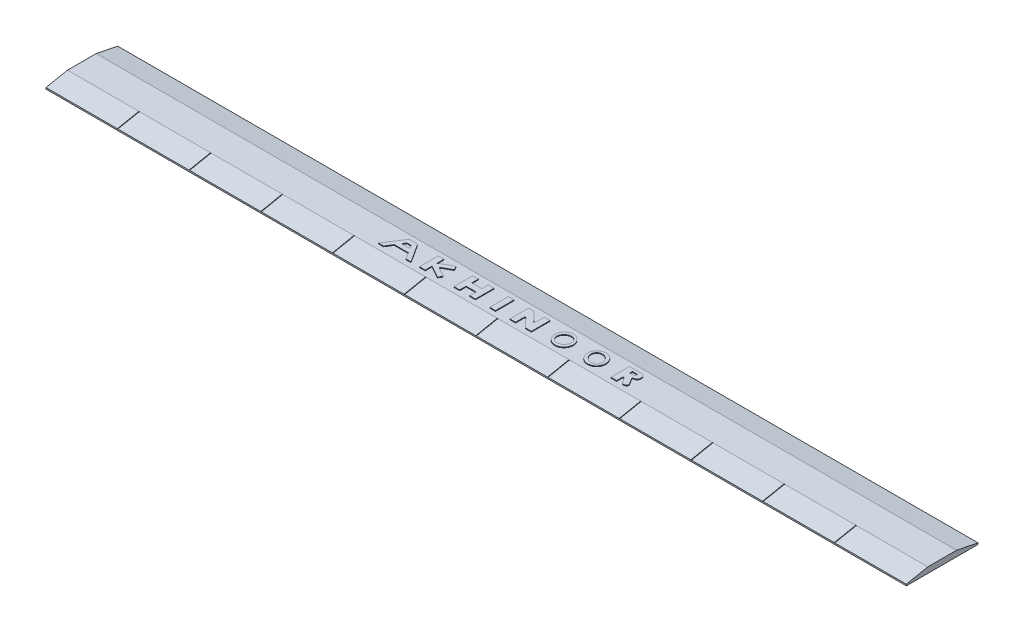
SolidWorks part; units mm, degrees
ref_plane "Front Plane" through (0, 0, 0) normal (0, 0, 1) x (1, 0, 0)
ref_plane "Top Plane" through (0, 0, 0) normal (0, 1, 0) x (1, 0, 0)
ref_plane "Right Plane" through (0, 0, 0) normal (1, 0, 0) x (0, 0, -1)
sketch "Sketch1" plane through (0, 0, 0) normal (0, 1, 0) x (1, 0, 0)
  line L0 (0, 0) -> (-304.8, 0)
  line L1 (-304.8, 0) -> (-304.8, 25.4)
  line L2 (-304.8, 25.4) -> (0, 25.4)
  line L3 (0, 25.4) -> (0, 0)
  dimension "D1" = 304.8
  dimension "D2" = 25.4
extrude "Boss-Extrude1" add sketch "Sketch1" along normal blind 2.032
sketch "Sketch2" plane through (0, 0, 0) normal (1, 0, 0) x (0, 0, -1)
  line L0 (0, 0.508) -> (7.62, 2.032)
  line L1 (0, 2.032) -> (0, 0) construction
  line L3 (0, 2.032) -> (25.4, 2.032) construction
  line L4 (17.78, 2.032) -> (25.4, 0.508)
  line L5 (25.4, 2.032) -> (25.4, 0) construction
  line L6 (25.4, 0.508) -> (25.4, 0)
  line L7 (25.4, 0) -> (0, 0)
  line L8 (0, 0) -> (0, 0.508)
  line L10 (7.62, 2.032) -> (12.7, 2.032)
  line L11 (17.78, 2.032) -> (12.7, 2.032)
  dimension "D1" = 0.508
  dimension "D2" = 5.08
extrude "Cut-Extrude2" cut sketch "Sketch2" against normal through all flip side to cut
sketch "Sketch4" plane through (0, 2.032, 0) normal (0, 1, 0) x (1, 0, 0)
  line L0 (-152.4, 17.78) -> (-152.4, 7.62) construction
  line L1 (-304.8, 17.78) -> (0, 17.78) construction
  line L2 (-304.8, 7.62) -> (0, 7.62) construction
  line L3 (-304.8, 16.002) -> (-144.272, 16.002) construction
  line L4 (-304.8, 17.78) -> (-304.8, 7.62) construction
  line L5 (0, 7.62) -> (0, 17.78) construction
  line L6 (0, 16.002) -> (0, 9.398)
  line L7 (0, 9.398) -> (-304.8, 9.398) construction
  line L8 (-304.8, 9.398) -> (-304.8, 16.002) construction
  line L9 (-304.8, 12.7) -> (-194.2687, 12.7) construction
  line L11 (-156.972, 16.002) -> (-154.94, 16.002)
  line L12 (-156.972, 16.002) -> (-156.972, 9.398)
  line L13 (-156.972, 9.398) -> (-154.94, 9.398)
  line L14 (-154.94, 16.002) -> (-154.94, 9.398)
  line L15 (-156.972, 16.002) -> (-154.94, 9.398) construction
  line L16 (-156.972, 9.398) -> (-154.94, 16.002) construction
  line L17 (-164.084, 16.002) -> (-162.052, 16.002)
  line L18 (-164.084, 16.002) -> (-164.084, 9.398)
  line L19 (-164.084, 9.398) -> (-162.052, 9.398)
  line L20 (-162.052, 16.002) -> (-162.052, 9.398)
  line L21 (-164.084, 16.002) -> (-162.052, 9.398) construction
  line L22 (-164.084, 9.398) -> (-162.052, 16.002) construction
  line L23 (-167.64, 13.716) -> (-164.084, 13.716)
  line L24 (-167.64, 13.716) -> (-167.64, 11.684)
  line L25 (-167.64, 11.684) -> (-164.084, 11.684)
  line L26 (-164.084, 13.716) -> (-164.084, 11.684)
  line L27 (-167.64, 13.716) -> (-164.084, 11.684) construction
  line L28 (-167.64, 11.684) -> (-164.084, 13.716) construction
  line L29 (-169.672, 16.002) -> (-167.64, 16.002)
  line L30 (-169.672, 16.002) -> (-169.672, 9.398)
  line L31 (-169.672, 9.398) -> (-167.64, 9.398)
  line L32 (-167.64, 16.002) -> (-167.64, 9.398)
  line L33 (-169.672, 16.002) -> (-167.64, 9.398) construction
  line L34 (-169.672, 9.398) -> (-167.64, 16.002) construction
  line L35 (-179.832, 16.002) -> (-181.864, 16.002)
  line L36 (-179.832, 16.002) -> (-179.832, 9.398)
  line L37 (-179.832, 9.398) -> (-181.864, 9.398)
  line L38 (-181.864, 16.002) -> (-181.864, 9.398)
  line L39 (-179.832, 16.002) -> (-181.864, 9.398) construction
  line L40 (-179.832, 9.398) -> (-181.864, 16.002) construction
  line L46 (-189.1051, 16.002) -> (-190.6291, 16.002)
  line L47 (-149.86, 16.002) -> (-147.828, 16.002)
  line L48 (-149.86, 16.002) -> (-149.86, 9.398)
  line L49 (-149.86, 9.398) -> (-147.828, 9.398)
  line L50 (-147.828, 12.4056) -> (-147.828, 9.398)
  line L51 (-149.86, 16.002) -> (-147.828, 9.398) construction
  line L52 (-149.86, 9.398) -> (-147.828, 16.002) construction
  line L54 (-144.272, 16.002) -> (-144.272, 12.8787)
  line L55 (-144.272, 9.398) -> (-142.24, 9.398)
  line L56 (-142.24, 16.002) -> (-142.24, 9.398)
  line L57 (-108.5727, 10.4151) -> (-110.0035, 12.7339)
  line L58 (-142.24, 16.002) -> (0, 16.002) construction
  line L59 (-111.7665, 13.97) -> (-110.4965, 13.97)
  line L60 (-114.0525, 9.398) -> (-112.0205, 9.398)
  line L61 (-114.0525, 9.398) -> (-114.0525, 16.002)
  line L62 (-114.0525, 16.002) -> (-111.1357, 16.002)
  line L63 (-112.0205, 9.398) -> (-112.0205, 11.3557)
  line L64 (-109.7345, 16.002) -> (-111.1357, 16.002)
  line L74 (-111.7665, 14.986) -> (-110.4965, 14.986)
  line L75 (-110.2425, 14.224) -> (-110.2425, 14.732)
  line L76 (-112.0205, 14.732) -> (-112.0205, 14.224)
  line L77 (-108.4645, 14.732) -> (-108.4645, 14.3913)
  line L78 (-109.7345, 13.1213) -> (-109.7873, 13.1213)
  line L79 (-179.832, 12.7) -> (-179.832, 16.002) construction
  line L80 (-179.7014, 13.6616) -> (-175.4926, 16.002)
  line L81 (-175.4926, 16.002) -> (-174.8754, 14.8921)
  line L82 (-174.974, 14.5466) -> (-177.8956, 12.922)
  line L84 (-177.8956, 12.478) -> (-174.974, 10.8534)
  line L85 (-174.8754, 10.5079) -> (-175.4926, 9.398)
  line L86 (-175.4926, 9.398) -> (-179.7014, 11.7384)
  line L87 (-179.832, 11.9604) -> (-179.832, 12.7)
  line L88 (-179.832, 12.7) -> (-179.832, 13.4396)
  line L89 (-189.1051, 16.002) -> (-184.8739, 9.398)
  line L94 (-184.8739, 9.398) -> (-186.6519, 9.398)
  line L98 (-194.6064, 9.398) -> (-196.3844, 9.398)
  line L99 (-196.3844, 9.398) -> (-192.1531, 16.002)
  line L101 (-190.6291, 16.002) -> (-192.1531, 16.002)
  line L102 (-186.9895, 12.7) -> (0, 12.7) construction
  line L103 (-194.6064, 9.398) -> (-193.2078, 11.6077)
  line L105 (-190.007, 14.478) -> (-191.2513, 14.478)
  line L107 (-189.7923, 14.3598) -> (-189.3366, 13.6397)
  line L108 (-191.7071, 13.2499) -> (-189.5512, 13.2499)
  line L110 (-188.2651, 11.7259) -> (-192.9932, 11.7259)
  line L112 (-191.9217, 13.6397) -> (-191.4659, 14.3598)
  line L113 (-188.0505, 11.6077) -> (-186.6519, 9.398)
  line L114 (-147.3894, 12.5801) -> (-144.4566, 9.4775)
  line L115 (-144.7106, 12.7042) -> (-147.828, 16.002)
  line L116 (-144.272, 16.002) -> (-142.24, 16.002)
  line L118 (-111.561, 11.5049) -> (-110.1647, 9.5826)
  arc A0 (-109.7345, 13.1213) -> (-108.4645, 14.3913) centre (-109.7345, 14.3913) ccw
  arc A1 (-109.7345, 16.002) -> (-108.4645, 14.732) centre (-109.7345, 14.732) cw
  arc A3 (-192.9932, 11.7259) -> (-193.2078, 11.6077) centre (-192.9932, 11.4719) ccw
  arc A4 (-188.0505, 11.6077) -> (-188.2651, 11.7259) centre (-188.2651, 11.4719) ccw
  arc A5 (-191.7071, 13.2499) -> (-191.9217, 13.6397) centre (-191.7071, 13.5039) cw
  arc A6 (-191.2513, 14.478) -> (-191.4659, 14.3598) centre (-191.2513, 14.224) ccw
  arc A7 (-189.7923, 14.3598) -> (-190.007, 14.478) centre (-190.007, 14.224) ccw
  arc A8 (-189.5512, 13.2499) -> (-189.3366, 13.6397) centre (-189.5512, 13.5039) ccw
  arc A9 (-174.8754, 14.8921) -> (-174.974, 14.5466) centre (-175.0974, 14.7686) cw
  arc A10 (-174.974, 10.8534) -> (-174.8754, 10.5079) centre (-175.0974, 10.6314) cw
  arc A11 (-179.7014, 11.7384) -> (-179.832, 11.9604) centre (-179.578, 11.9604) cw
  arc A12 (-179.7014, 13.6616) -> (-179.832, 13.4396) centre (-179.578, 13.4396) ccw
  arc A13 (-177.8956, 12.478) -> (-177.8956, 12.922) centre (-177.7722, 12.7) cw
  arc A14 (-144.4566, 9.4775) -> (-144.272, 9.398) centre (-144.272, 9.652) ccw
  arc A15 (-147.3894, 12.5801) -> (-147.828, 12.4056) centre (-147.574, 12.4056) ccw
  arc A16 (-144.7106, 12.7042) -> (-144.272, 12.8787) centre (-144.526, 12.8787) ccw
  arc A17 (-112.0205, 14.224) -> (-111.7665, 13.97) centre (-111.7665, 14.224) ccw
  arc A18 (-112.0205, 14.732) -> (-111.7665, 14.986) centre (-111.7665, 14.732) cw
  arc A19 (-110.4965, 14.986) -> (-110.2425, 14.732) centre (-110.4965, 14.732) cw
  arc A20 (-110.2425, 14.224) -> (-110.4965, 13.97) centre (-110.4965, 14.224) cw
  arc A21 (-110.0035, 12.7339) -> (-109.7873, 13.1213) centre (-109.7873, 12.8673) cw
  arc A23 (-112.0205, 11.3557) -> (-111.561, 11.5049) centre (-111.7665, 11.3557) cw
  arc A25 (-110.1647, 9.5826) -> (-108.5727, 10.4151) centre (-109.6349, 10.5079) ccw
  ellipse E0 centre (-133.9231, 12.7) end of major axis (-133.9231, 9.398) minor radius 3.2369
  ellipse E1 centre (-133.9231, 12.7) end of major axis (-132.0191, 14.2717) minor radius 2.1571
  ellipse E2 centre (-122.3694, 12.7) end of major axis (-124.2733, 14.2717) minor radius 2.1571
  ellipse E3 centre (-122.3694, 12.7) end of major axis (-122.3694, 9.398) minor radius 3.2369
  point P16 (-155.956, 12.7)
  point P21 (-163.068, 12.7)
  point P26 (-165.862, 12.7)
  point P31 (-168.656, 12.7)
  point P36 (-180.848, 12.7)
  point P41 (-189.484, 12.7)
  point P46 (-148.844, 12.7)
  point P101 (-178.2948, 12.7)
  point P107 (-190.6291, 11.7259)
  point P113 (-190.6291, 13.2499)
  point P114 (-190.6291, 14.478)
  point P120 (-108.4645, 13.1213)
  point P123 (-108.4645, 16.002)
  point P131 (-192.1684, 13.2499)
  point P134 (-191.3911, 14.478)
  point P137 (-189.8671, 14.478)
  point P140 (-189.0898, 13.2499)
  point P143 (-174.752, 14.6701)
  point P146 (-174.752, 10.7299)
  point P149 (-179.832, 11.811)
  point P152 (-179.832, 13.589)
  point P155 (-178.2948, 12.7)
  point P164 (-112.0205, 13.97)
  point P171 (-110.2425, 13.97)
  point P174 (-110.2425, 13.1213)
  point P177 (-110.0306, 9.398)
  point P180 (-112.0205, 12.1376)
  dimension "D15" = 1.27
  dimension "D33" = 1.27
  dimension "D37" = 0.254
  dimension "D1" = 1.778
  dimension "D2" = 1.778
  dimension "D3" = 2.032
  dimension "D4" = 0
  dimension "D5" = 7.62
  dimension "D6" = 5.08
  dimension "D7" = 5.08
  dimension "D8" = 2.54
  dimension "D9" = 7.62
  dimension "D10" = 5.08
  dimension "D11" = 5.08
  dimension "D12" = 5.08
  dimension "D14" = 5.588
  dimension ".07" = 1.778
  dimension "D16" = 10.16
  dimension "D17" = 1.778
  dimension "D18" = 1.524
  dimension "D19" = 3.0099
  dimension "D20" = 5.08
  dimension "D21" = 180
  dimension "D22" = 1.524
  dimension "D23" = 3.048
  dimension "D24" = 1.524
  dimension "D25" = 1.778
  dimension "D26" = 1.2281
  dimension "D27" = 3.0786
  dimension "D28" = 1.524
  dimension "D29" = 2.032
  dimension "D30" = 2.032
  dimension "D31" = 2.032
  dimension "D32" = 2.8807
  dimension "D34" = 0.4213
  dimension "D35" = 3.81
  dimension "D36" = 2.032
extrude "Boss-Extrude2" add sketch "Sketch4" along normal blind 0.254 contours L35 L38 L37 L36 | L84 A13 L82 A9 L81 L80 A12 L36 A11 L86 L85 A10 | L32 L29 L30 L31 L24 | L20 L17 L18 L19 | L24 L25 L18 L23 | L14 L11 L12 L13 | A16 L115 L47 L48 L49 L50 A15 L114 A14 L55 L56 L116 L54 | E0 E1 | E3 E2 | L118 A25 L57 A21 L78 A0 L77 A1 L64 L62 L61 L60 L63 A23 L75 A20 L59 A17 L76 A18 L74 A19 | A4 L113 L94 L89 L46 L101 L99 L98 L103 A3 L110 A8 L108 A5 L112 A6 L105 A7 L107
sketch "Sketch5" plane through (0, 0.4885, 0.0977) normal (0, 0.9806, 0.1961) x (1, 0, 0)
  line L0 (-304.8, 3.9851) -> (0, 3.9851) construction
  line L1 (-304.8, 7.8705) -> (-304.8, 0.0996) construction
  line L2 (0, 7.8705) -> (0, 0.0996) construction
  line L3 (-304.8, 0.0996) -> (0, 0.0996) construction
  line L4 (-127.127, 7.8705) -> (-126.873, 7.8705)
  line L5 (-127.127, 7.8705) -> (-127.127, 0.0996)
  line L6 (-127.127, 0.0996) -> (-126.873, 0.0996)
  line L7 (-126.873, 7.8705) -> (-126.873, 0.0996)
  line L8 (-127.127, 7.8705) -> (-126.873, 0.0996) construction
  line L9 (-127.127, 0.0996) -> (-126.873, 7.8705) construction
  line L11 (-228.727, 7.8705) -> (-228.473, 7.8705)
  line L12 (-228.727, 7.8705) -> (-228.727, 0.0996)
  line L13 (-228.727, 0.0996) -> (-228.473, 0.0996)
  line L14 (-228.473, 7.8705) -> (-228.473, 0.0996)
  line L15 (-228.727, 7.8705) -> (-228.473, 0.0996) construction
  line L16 (-228.727, 0.0996) -> (-228.473, 7.8705) construction
  line L17 (-203.327, 7.8705) -> (-203.073, 7.8705)
  line L18 (-203.327, 7.8705) -> (-203.327, 0.0996)
  line L19 (-203.327, 0.0996) -> (-203.073, 0.0996)
  line L20 (-203.073, 7.8705) -> (-203.073, 0.0996)
  line L21 (-203.327, 7.8705) -> (-203.073, 0.0996) construction
  line L22 (-203.327, 0.0996) -> (-203.073, 7.8705) construction
  line L23 (-76.327, 7.8705) -> (-76.073, 7.8705)
  line L24 (-76.327, 7.8705) -> (-76.327, 0.0996)
  line L25 (-76.327, 0.0996) -> (-76.073, 0.0996)
  line L26 (-76.073, 7.8705) -> (-76.073, 0.0996)
  line L27 (-76.327, 7.8705) -> (-76.073, 0.0996) construction
  line L28 (-76.327, 0.0996) -> (-76.073, 7.8705) construction
  line L29 (-177.927, 7.8705) -> (-177.673, 7.8705)
  line L30 (-177.927, 7.8705) -> (-177.927, 0.0996)
  line L31 (-177.927, 0.0996) -> (-177.673, 0.0996)
  line L32 (-177.673, 7.8705) -> (-177.673, 0.0996)
  line L33 (-177.927, 7.8705) -> (-177.673, 0.0996) construction
  line L34 (-177.927, 0.0996) -> (-177.673, 7.8705) construction
  line L35 (-50.927, 7.8705) -> (-50.673, 7.8705)
  line L36 (-50.927, 7.8705) -> (-50.927, 0.0996)
  line L37 (-50.927, 0.0996) -> (-50.673, 0.0996)
  line L38 (-50.673, 7.8705) -> (-50.673, 0.0996)
  line L39 (-50.927, 7.8705) -> (-50.673, 0.0996) construction
  line L40 (-50.927, 0.0996) -> (-50.673, 7.8705) construction
  line L41 (-25.527, 7.8705) -> (-25.273, 7.8705)
  line L42 (-25.527, 7.8705) -> (-25.527, 0.0996)
  line L43 (-25.527, 0.0996) -> (-25.273, 0.0996)
  line L44 (-25.273, 7.8705) -> (-25.273, 0.0996)
  line L45 (-25.527, 7.8705) -> (-25.273, 0.0996) construction
  line L46 (-25.527, 0.0996) -> (-25.273, 7.8705) construction
  line L53 (-101.727, 7.8705) -> (-101.473, 7.8705)
  line L54 (-101.727, 7.8705) -> (-101.727, 0.0996)
  line L55 (-101.727, 0.0996) -> (-101.473, 0.0996)
  line L56 (-101.473, 7.8705) -> (-101.473, 0.0996)
  line L57 (-101.727, 7.8705) -> (-101.473, 0.0996) construction
  line L58 (-101.727, 0.0996) -> (-101.473, 7.8705) construction
  line L59 (-152.527, 7.8705) -> (-152.273, 7.8705)
  line L60 (-152.527, 7.8705) -> (-152.527, 0.0996)
  line L61 (-152.527, 0.0996) -> (-152.273, 0.0996)
  line L62 (-152.273, 7.8705) -> (-152.273, 0.0996)
  line L63 (-152.527, 7.8705) -> (-152.273, 0.0996) construction
  line L64 (-152.527, 0.0996) -> (-152.273, 7.8705) construction
  line L65 (-279.527, 7.8705) -> (-279.273, 7.8705)
  line L66 (-279.527, 7.8705) -> (-279.527, 0.0996)
  line L67 (-279.527, 0.0996) -> (-279.273, 0.0996)
  line L68 (-279.273, 7.8705) -> (-279.273, 0.0996)
  line L69 (-279.527, 7.8705) -> (-279.273, 0.0996) construction
  line L70 (-279.527, 0.0996) -> (-279.273, 7.8705) construction
  line L71 (-254.127, 7.8705) -> (-253.873, 7.8705)
  line L72 (-254.127, 7.8705) -> (-254.127, 0.0996)
  line L73 (-254.127, 0.0996) -> (-253.873, 0.0996)
  line L74 (-253.873, 7.8705) -> (-253.873, 0.0996)
  line L75 (-254.127, 7.8705) -> (-253.873, 0.0996) construction
  line L76 (-254.127, 0.0996) -> (-253.873, 7.8705) construction
  point P6 (-127, 3.9851)
  point P13 (-228.6, 3.9851)
  point P18 (-203.2, 3.9851)
  point P23 (-76.2, 3.9851)
  point P28 (-177.8, 3.9851)
  point P33 (-50.8, 3.9851)
  point P38 (-25.4, 3.9851)
  point P43 (-203.1479, 3.9851)
  point P48 (-101.6, 3.9851)
  point P53 (-152.4, 3.9851)
  point P58 (-279.4, 3.9851)
  point P63 (-254, 3.9851)
  point P78 (-279.4, 0.0996)
  point P79 (-254, 0.0996)
  dimension "D1" = 0.254
  dimension "D2" = 25.4
  dimension "D3" = 25.4
  dimension "D4" = 25.4
  dimension "D5" = 127
  dimension "D6" = 25.4
  dimension "D7" = 152.4
  dimension "D8" = 177.8
  dimension "D9" = 203.2
  dimension "D10" = 228.6
  dimension "D11" = 254
  dimension "D12" = 279.4
  dimension "D13" = 7.7709
extrude "Cut-Extrude9" cut sketch "Sketch5" against normal blind 0.1778
sketch "Sketch6" plane through (0, 0, 0) normal (0, 1, 0) x (1, 0, 0)
  line L0 (-304.8, 12.7) -> (0, 12.7) construction
  line L1 (-304.8, 17.78) -> (-304.8, 7.62) construction
  line L2 (0, 7.62) -> (0, 17.78) construction
